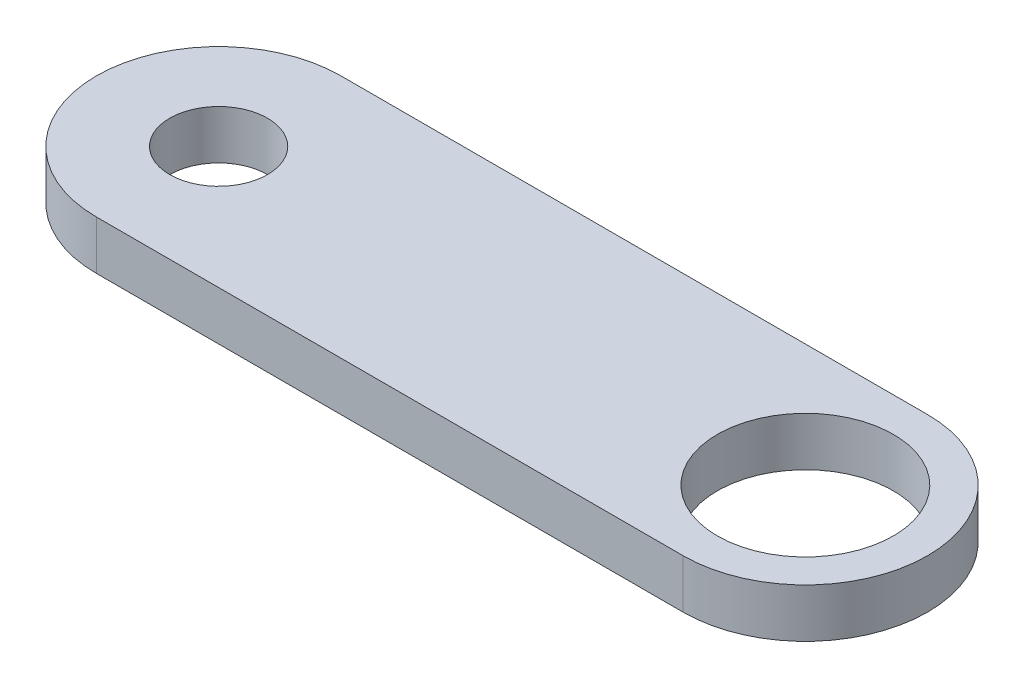
SolidWorks part; units mm, degrees
ref_plane "Front Plane" through (0, 0, 0) normal (0, 0, 1) x (1, 0, 0)
ref_plane "Top Plane" through (0, 0, 0) normal (0, 1, 0) x (1, 0, 0)
ref_plane "Right Plane" through (0, 0, 0) normal (1, 0, 0) x (0, 0, -1)
sketch "Sketch1" plane through (0, 0, 0) normal (0, 1, 0) x (1, 0, 0)
  line L0 (0, 0) -> (60, 0) construction
  line L1 (0, 12.5) -> (60, 12.5)
  line L2 (0, -12.5) -> (60, -12.5)
  circle A0 centre (0, 0) radius 5
  circle A1 centre (60, 0) radius 9
  arc A3 (0, 12.5) -> (0, -12.5) centre (0, 0) ccw
  arc A4 (60, -12.5) -> (60, 12.5) centre (60, 0) ccw
  point P5 (30, 0)
  dimension "D1" = 10
  dimension "D2" = 18
  dimension "D3" = 60
  dimension "D4" = 12.5
extrude "Boss-Extrude1" add sketch "Sketch1" along normal blind 5
